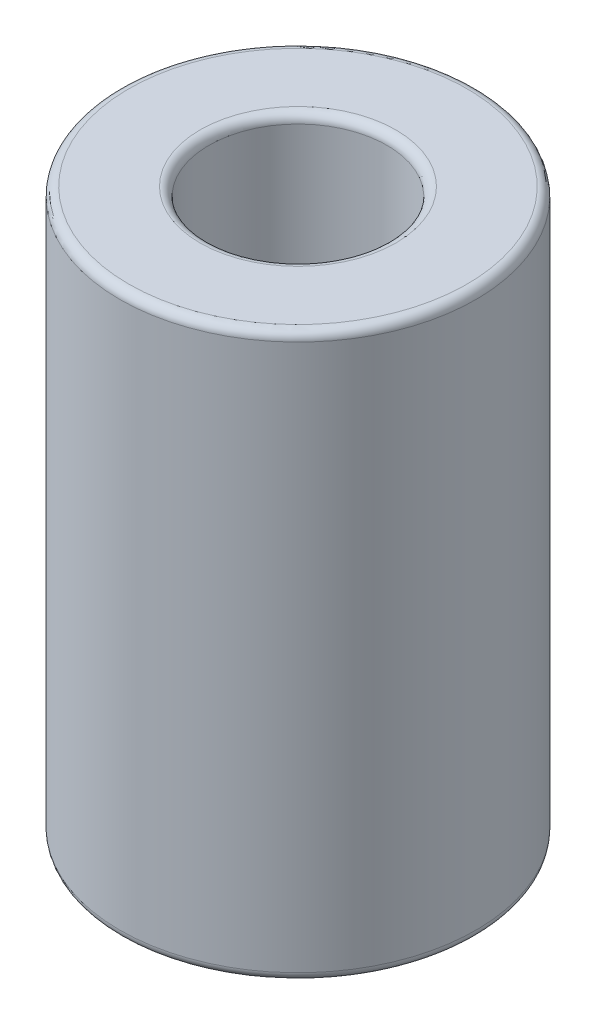
SolidWorks part; units mm, degrees
ref_plane "Front Plane" through (0, 0, 0) normal (0, 0, 1) x (1, 0, 0)
ref_plane "Top Plane" through (0, 0, 0) normal (0, 1, 0) x (1, 0, 0)
ref_plane "Right Plane" through (0, 0, 0) normal (1, 0, 0) x (0, 0, -1)
sketch "Sketch1" plane through (0, 0, 0) normal (0, 1, 0) x (1, 0, 0)
  circle A0 centre (0, 0) radius 3
  circle A1 centre (0, 0) radius 6
  dimension "D1" = 6
  dimension "D2" = 12
extrude "Boss-Extrude1" add sketch "Sketch1" along normal blind 19
fillet "Fillet1" radius 0.3 4 edges at (0, 0, 6) (0, 0, 3) (0, 19, 3) (0, 19, 6)
